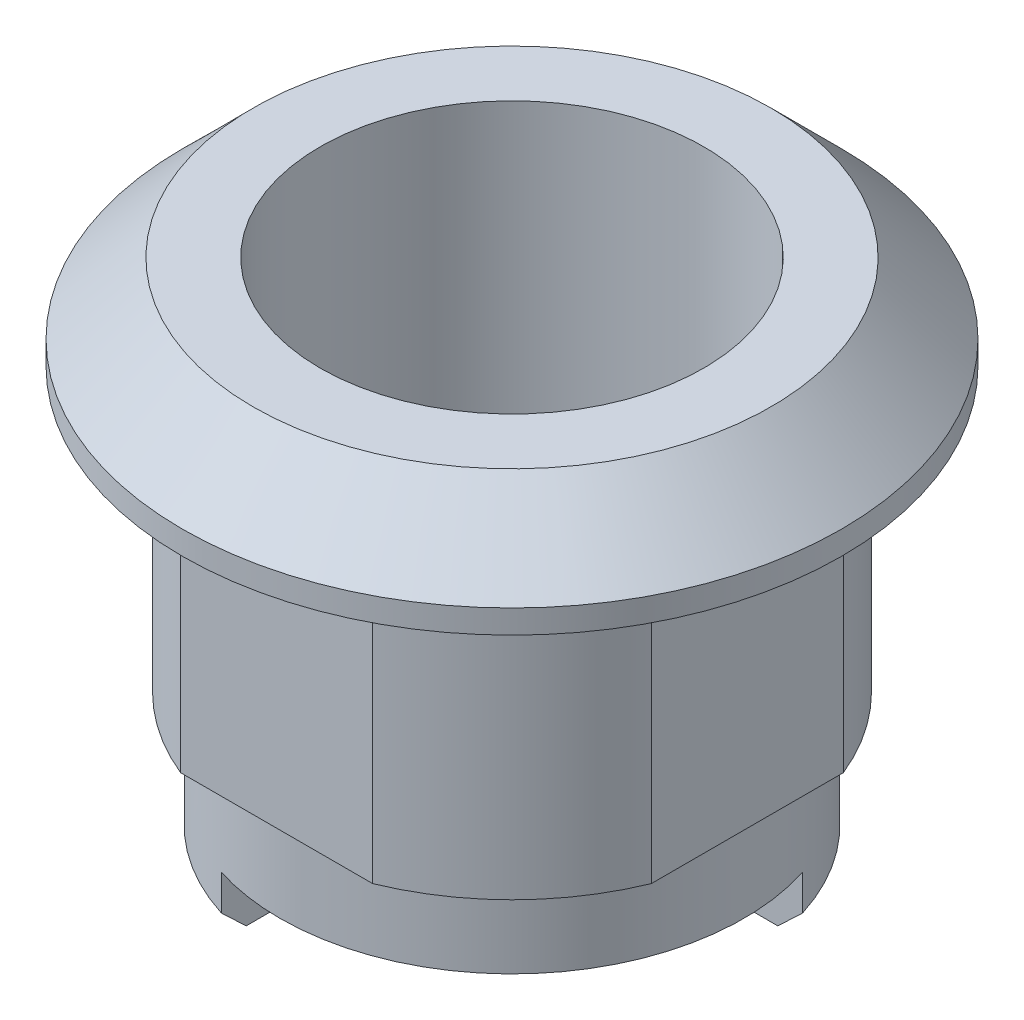
SolidWorks part; units mm, degrees
ref_plane "Piano frontale" through (0, 0, 0) normal (0, 0, 1) x (1, 0, 0)
ref_plane "Piano superiore" through (0, 0, 0) normal (0, 1, 0) x (1, 0, 0)
ref_plane "Piano destro" through (0, 0, 0) normal (1, 0, 0) x (0, 0, -1)
sketch "Schizzo1" plane through (0, 0, 0) normal (0, 0, 1) x (1, 0, 0)
  line L0 (0, 15.2972) -> (0, -14.0734) construction
  line L1 (8.15, -4.65) -> (8.15, 10.95)
  line L2 (8.15, 10.95) -> (14, 10.95)
  line L3 (14, 10.95) -> (14, 6.95)
  line L4 (14, 6.95) -> (10.8, 6.95)
  line L6 (9.85, -10.95) -> (5.1, -10.95)
  line L7 (5.1, -10.95) -> (5.1, -4.65)
  line L8 (5.1, -4.65) -> (8.15, -4.65)
  line L9 (9.85, -10.95) -> (9.85, -5.05)
  line L10 (9.85, -5.05) -> (10.8, -5.05)
  line L11 (10.8, -5.05) -> (10.8, 6.95)
  point P12 (12.4, 6.95)
  dimension "D1" = 28
  dimension "D2" = 19.7
  dimension "D3" = 21.6
  dimension "D4" = 4
  dimension "D5" = 16.3
  dimension "D6" = 10.2
  dimension "D7" = 15.6
  dimension "D8" = 21.9
  dimension "D9" = 10.95
  dimension "D10" = 5.9
revolve "Rivoluzione1" add sketch "Schizzo1" angle 360 about L0
chamfer "Smusso1" distance 3 angle 45 1 edges at (0, 10.95, 14)
sketch "Schizzo2" plane through (0, -10.95, 0) normal (0, -1, 0) x (1, 0, 0)
  line L1 (-10, 10) -> (10, 10)
  line L2 (-10, 10) -> (-10, -10)
  line L3 (-10, -10) -> (10, -10)
  line L4 (10, 10) -> (10, -10)
  line L5 (-10, 10) -> (10, -10) construction
  line L6 (-10, -10) -> (10, 10) construction
  circle A0 centre (0, 0) radius 18.6794
  point P0 (0, 0)
  dimension "D1" = 20
extrude "Taglio-Estrusione1" cut sketch "Schizzo2" against normal up to surface (17.9 mm away) up to face at (0, 6.95, 14)
sketch "Schizzo3" plane through (0, -10.95, 0) normal (0, -1, 0) x (1, 0, 0)
  line L1 (-2.95, -2.95) -> (17.05, -2.95)
  line L2 (-2.95, -2.95) -> (-2.95, 17.05)
  line L3 (-2.95, 17.05) -> (17.05, 17.05)
  line L4 (17.05, -2.95) -> (17.05, 17.05)
  circle A1 centre (0, 0) radius 9.85 construction
  circle A3 centre (0, 0) radius 9.85 construction
  dimension "D1" = 6.9
  dimension "D2" = 6.9
  dimension "D3" = 20
  dimension "D4" = 20
extrude "Taglio-Estrusione2" cut sketch "Schizzo3" against normal blind 2.5
chamfer "Smusso2" distance 1 angle 45 1 edges at (-6.965, -10.95, -6.965)
move or copy body "Corpo-Sposta/copia1" [suppressed] bodies to move or copy 103
equation "\"D9@Schizzo1\"=\"D8@Schizzo1\"/2"
